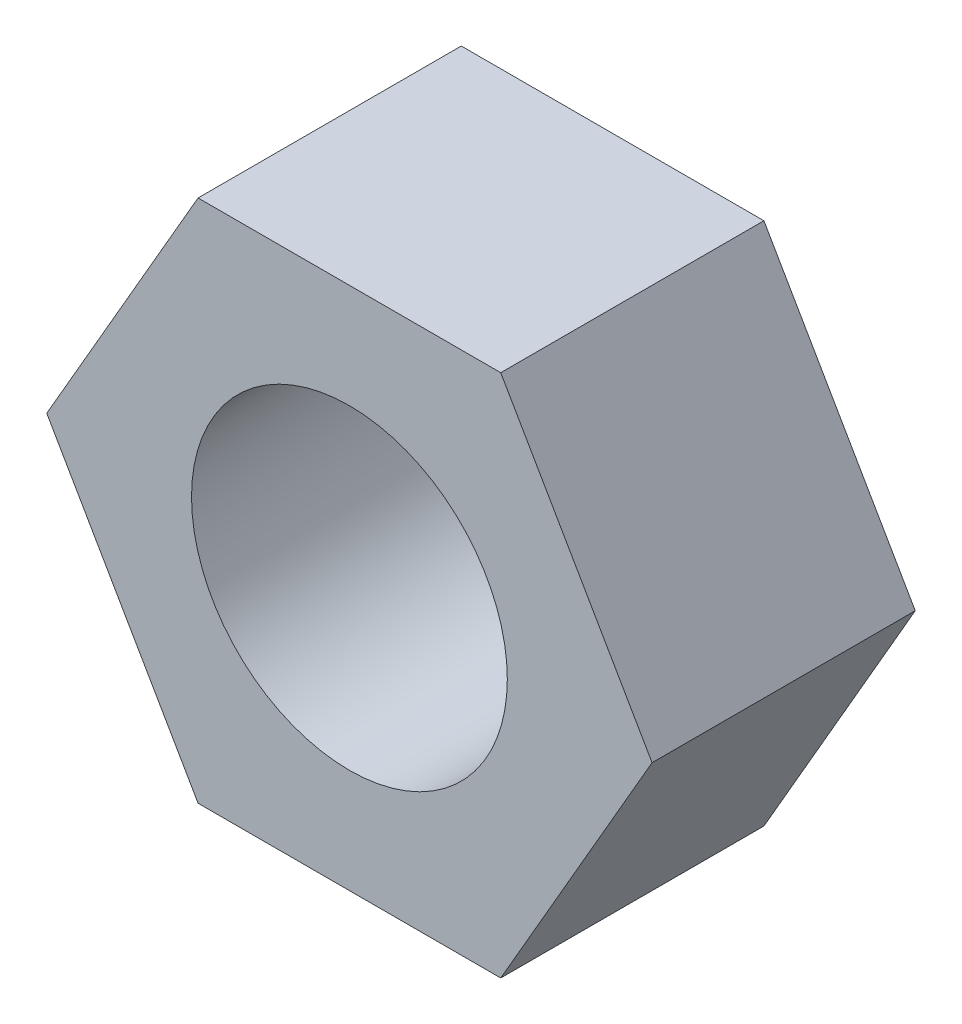
SolidWorks part; units mm, degrees
ref_plane "Front Plane" through (0, 0, 0) normal (0, 0, 1) x (1, 0, 0)
ref_plane "Top Plane" through (0, 0, 0) normal (0, 1, 0) x (1, 0, 0)
ref_plane "Right Plane" through (0, 0, 0) normal (1, 0, 0) x (0, 0, -1)
sketch "Sketch1" plane through (0, 0, 0) normal (0, 0, 1) x (1, 0, 0)
  line L1 (-2.875, 4.9796) -> (-5.75, 0)
  line L2 (-5.75, 0) -> (-2.875, -4.9796)
  line L3 (-2.875, -4.9796) -> (2.875, -4.9796)
  line L4 (2.875, -4.9796) -> (5.75, 0)
  line L5 (5.75, 0) -> (2.875, 4.9796)
  line L6 (2.875, 4.9796) -> (-2.875, 4.9796)
  circle A0 centre (0, 0) radius 5.75 construction
  circle A1 centre (0, 0) radius 3
  dimension "D1" = 11.5
  dimension "D2" = 6
extrude "Boss-Extrude1" add sketch "Sketch1" along normal blind 5
